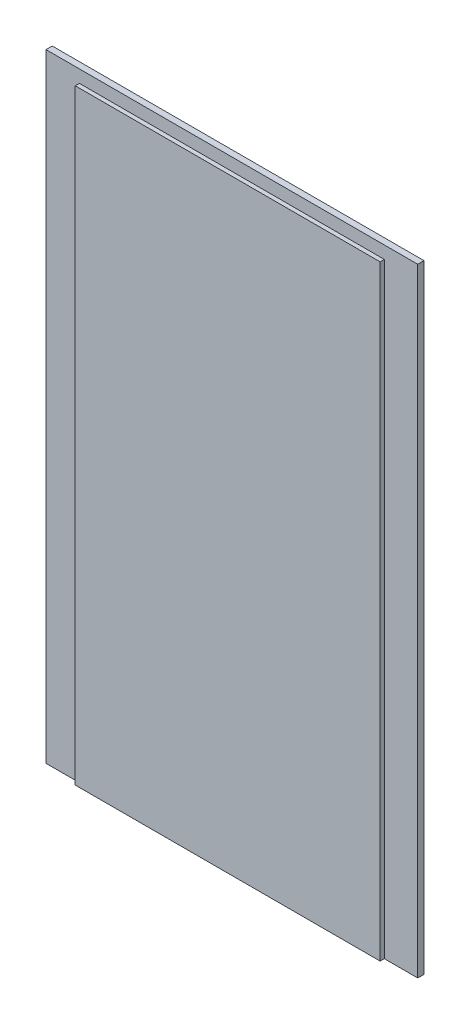
SolidWorks part; units mm, degrees
ref_plane "Спереди" through (0, 0, 0) normal (0, 0, 1) x (1, 0, 0)
ref_plane "Сверху" through (0, 0, 0) normal (0, 1, 0) x (1, 0, 0)
ref_plane "Справа" through (0, 0, 0) normal (1, 0, 0) x (0, 0, -1)
sketch "Эскиз5" plane through (0, 0, 0) normal (0, 1, 0) x (1, 0, 0)
  line L0 (36.5, 3.5) -> (-36.5, 3.5)
  line L1 (-36.5, 3.5) -> (-36.5, 2.5)
  line L2 (-36.5, 2.5) -> (-44.5, 2.5)
  line L3 (-44.5, 2.5) -> (-44.5, 1)
  line L4 (-44.5, 1) -> (-36.5, 1)
  line L5 (-36.5, 1) -> (-36.5, 0)
  line L6 (-36.5, 0) -> (36.5, 0)
  line L7 (0, 0) -> (0, 3.5) construction
  line L8 (36.5, 1) -> (36.5, 0)
  line L9 (44.5, 1) -> (36.5, 1)
  line L10 (44.5, 2.5) -> (44.5, 1)
  line L11 (36.5, 2.5) -> (44.5, 2.5)
  line L12 (36.5, 3.5) -> (36.5, 2.5)
  dimension "D1" = 1.5
  dimension "D2" = 8
  dimension "D3" = 36.5
  dimension "D4" = 3.5
extrude "Бобышка-Вытянуть1" add sketch "Эскиз5" along normal blind 145
sketch "Эскиз6" plane through (0, 145, 0) normal (0, 1, 0) x (1, 0, 0)
  line L1 (-44.5, 1) -> (44.5, 1)
  line L2 (-44.5, 1) -> (-44.5, 2.5)
  line L3 (-44.5, 2.5) -> (44.5, 2.5)
  line L4 (44.5, 1) -> (44.5, 2.5)
extrude "Бобышка-Вытянуть2" add sketch "Эскиз6" along normal blind 3
sketch "Эскиз7" plane through (0, 0, -3.5) normal (0, 0, -1) x (-1, 0, 0)
  line L0 (36.5, 72.5) -> (-36.5, 72.5) construction
  line L1 (36.5, 145) -> (36.5, 0) construction
  line L2 (-36.5, 145) -> (-36.5, 0) construction
  text T0 "<b>MIPT</b>\r\n<b>СОЛОНКА</b>\r\n<b>ОТ КОМАНДЫ</b>\r\n<b>\"ПИВО\"</b>" font "Century Gothic" height 3.5
extrude "Бобышка-Вытянуть3" add sketch "Эскиз7" along normal blind 3
